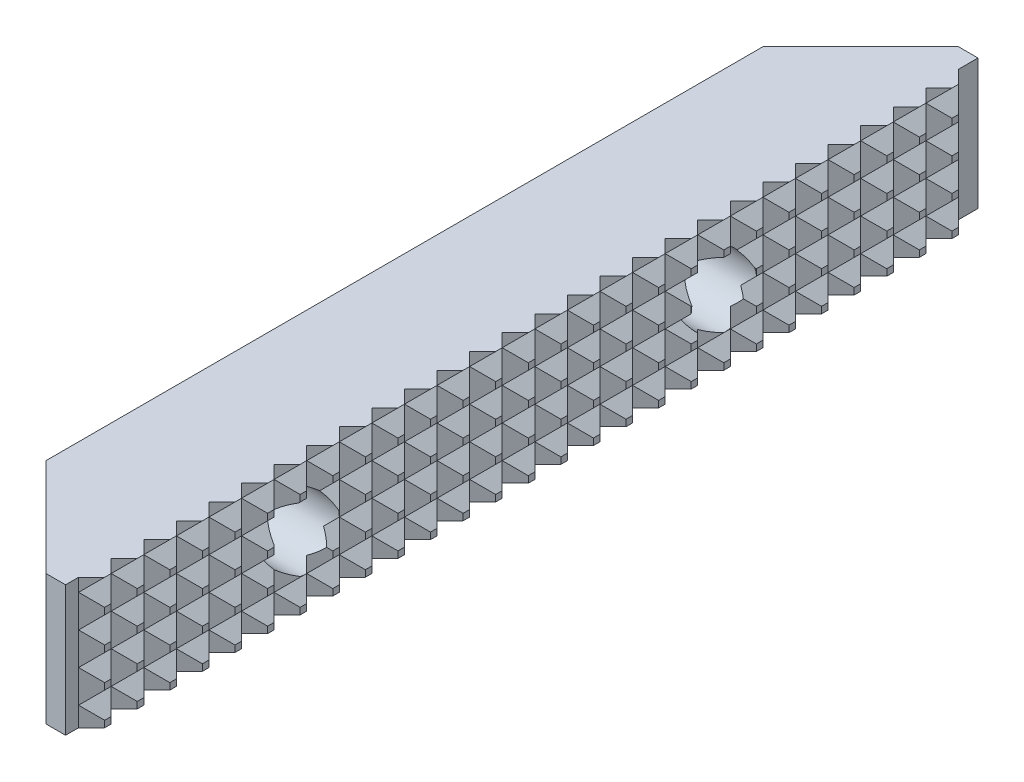
SolidWorks part; units mm, degrees
ref_plane "Ebene vorne" through (0, 0, 0) normal (0, 0, 1) x (1, 0, 0)
ref_plane "Ebene oben" through (0, 0, 0) normal (0, 1, 0) x (1, 0, 0)
ref_plane "Ebene rechts" through (0, 0, 0) normal (1, 0, 0) x (0, 0, -1)
sketch "Skizze1" plane through (0, 0, 0) normal (0, 0, 1) x (1, 0, 0)
  line L1 (-5, 5) -> (5, 5)
  line L2 (-5, 5) -> (-5, -5)
  line L3 (-5, -5) -> (5, -5)
  line L4 (5, 5) -> (5, -5)
  line L5 (-5, 5) -> (5, -5) construction
  line L6 (-5, -5) -> (5, 5) construction
  point P0 (0, 0)
  dimension "D1" = 10
  dimension "D2" = 10
extrude "Aufsatz-Linear austragen1" add sketch "Skizze1" along normal blind 70
sketch "Skizze2" plane through (5, 0, 0) normal (1, 0, 0) x (0, 0, -1)
  line L0 (-52.5, 0) -> (-20.5, 0)
  line L2 (-70, -5) -> (-70, 5) construction
  line L3 (0, -5) -> (0, 5) construction
  circle A0 centre (-52.5, 0) radius 1.5
  circle A1 centre (-20.5, 0) radius 1.5
  dimension "D4" = 3
  dimension "D5" = 3
  dimension "D1" = 32
  dimension "D2" = 17.5
  dimension "D3" = 20.5
extrude "Schnitt-Linear austragen1" cut sketch "Skizze2" against normal blind 70 contours A1 | A0
sketch "Skizze3" plane through (0, 0, 70) normal (0, 0, 1) x (1, 0, 0)
  line L0 (5, 5) -> (4, 4)
  line L1 (4, 4) -> (5, 3)
  line L2 (5, -5) -> (5, 5) construction
  line L3 (5, 5) -> (5, 3)
  dimension "D1" = 2
extrude "Schnitt-Linear austragen2" cut sketch "Skizze3" against normal through all both and the other way through all
pattern_linear "Lineares Muster1" count 4 spacing 2.5 along (0, -1, 0) of "Schnitt-Linear austragen2"
sketch "Skizze4" plane through (0, 5, 0) normal (0, 1, 0) x (1, 0, 0)
  line L0 (5, -70) -> (4, -69)
  line L1 (4, -69) -> (5, -68)
  line L2 (5, -70) -> (5, 0) construction
  line L3 (5, -68) -> (5, -70)
  dimension "D1" = 2
extrude "Schnitt-Linear austragen3" cut sketch "Skizze4" against normal through all both
pattern_linear "Lineares Muster2" count 28 spacing 2.5 along (0, 0, -1) of "Schnitt-Linear austragen3"
sketch "Skizze6" plane through (5, 0, 0) normal (1, 0, 0) x (0, 0, -1)
  circle A0 centre (-52.5, 0) radius 2.5
  circle A1 centre (-20.5, 0) radius 2.5
extrude "Schnitt-Linear austragen4" cut sketch "Skizze6" against normal blind 5
sketch "Skizze7" plane through (0, -5, 0) normal (0, -1, 0) x (1, 0, 0)
  line L1 (4, 1.5) -> (6.3575, 1.5)
  line L2 (4, 1.5) -> (4, -0.7008)
  line L3 (4, -0.7008) -> (6.3575, -0.7008)
  line L4 (6.3575, 1.5) -> (6.3575, -0.7008)
  line L5 (4, 69) -> (5.1788, 69)
  line L6 (4, 69) -> (4, 70.7729)
  line L7 (4, 70.7729) -> (5.1788, 70.7729)
  line L8 (5.1788, 69) -> (5.1788, 70.7729)
extrude "Schnitt-Linear austragen5" cut sketch "Skizze7" against normal through all
chamfer "Fase1" distance 7.5 angle 45 2 edges at (-5, 0, 0) (-5, 0, 70)
